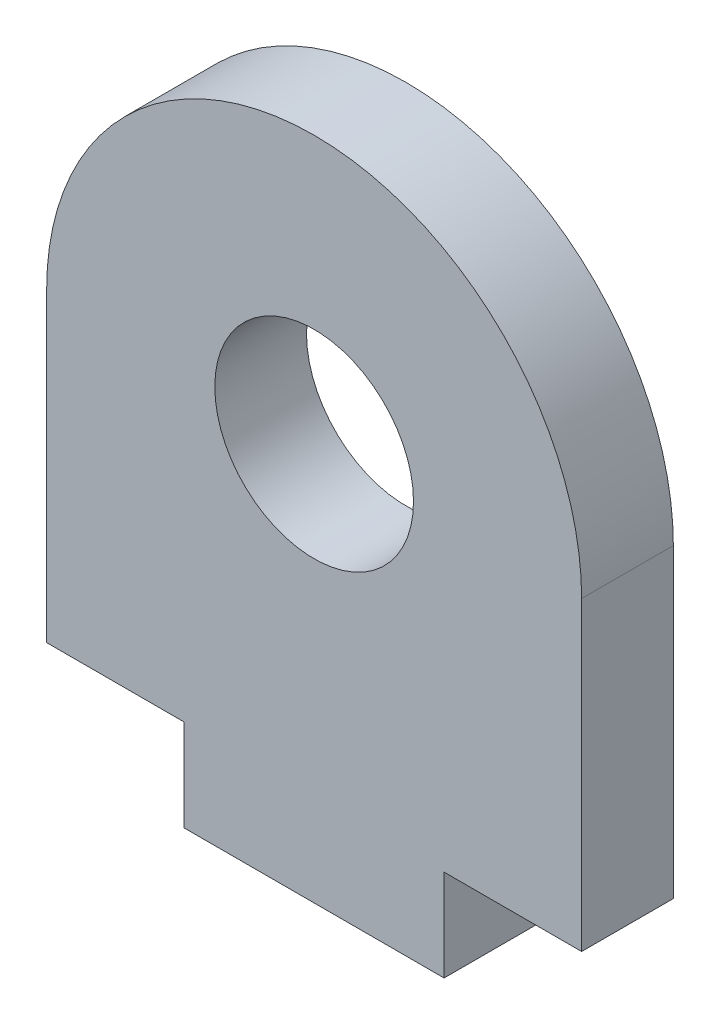
SolidWorks part; units mm, degrees
material "Plain Carbon Steel"
ref_plane "Front Plane" through (0, 0, 0) normal (0, 0, 1) x (1, 0, 0)
ref_plane "Top Plane" through (0, 0, 0) normal (0, 1, 0) x (1, 0, 0)
ref_plane "Right Plane" through (0, 0, 0) normal (1, 0, 0) x (0, 0, -1)
sketch "Sketch1" plane through (0, 0, 0) normal (0, 0, 1) x (1, 0, 0)
  line L0 (-17.5, 0) -> (-17.5, -20)
  line L1 (-17.5, -20) -> (-8.5, -20)
  line L2 (-8.5, -20) -> (-8.5, -26)
  line L3 (-8.5, -26) -> (8.5, -26)
  line L4 (8.5, -26) -> (8.5, -20)
  line L5 (8.5, -20) -> (17.5, -20)
  line L6 (17.5, -20) -> (17.5, 0)
  line L7 (0, 0) -> (0, -26) construction
  circle A0 centre (0, 0) radius 6.5
  arc A1 (17.5, 0) -> (-17.5, 0) centre (0, 0) ccw
  dimension "D1" = 35
  dimension "D5" = 13
  dimension "D2" = 17
  dimension "D3" = 20
  dimension "D4" = 6
extrude "Boss-Extrude1" add sketch "Sketch1" along normal blind 6
